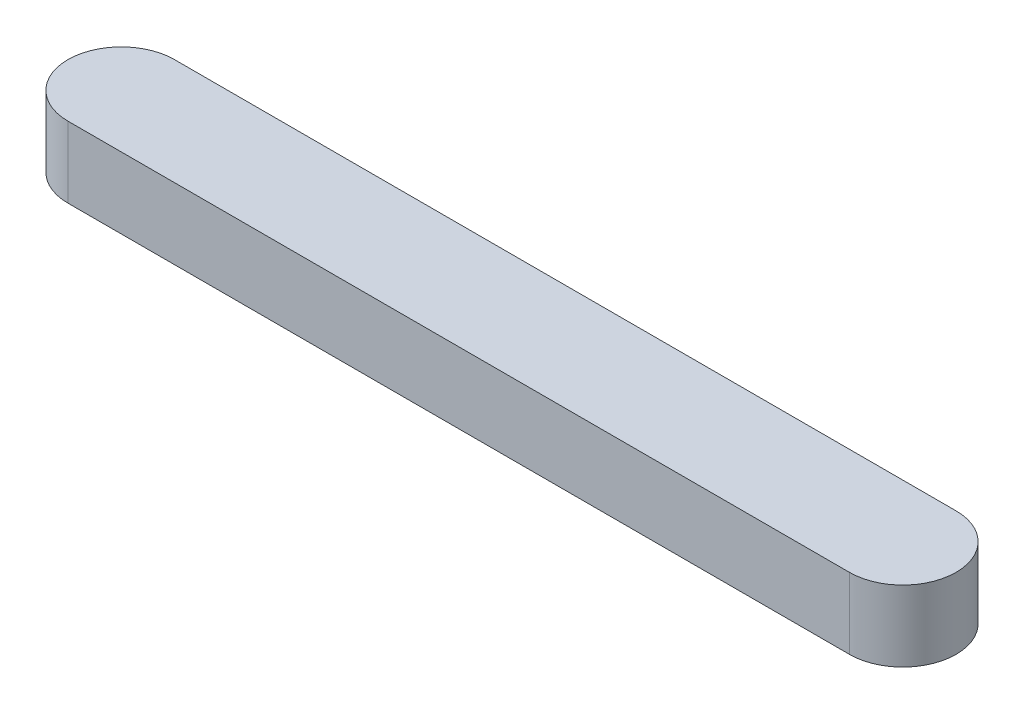
SolidWorks part; units mm, degrees
material "St-52"
ref_plane "Front Plane" through (0, 0, 0) normal (0, 0, 1) x (1, 0, 0)
ref_plane "Top Plane" through (0, 0, 0) normal (0, 1, 0) x (1, 0, 0)
ref_plane "Right Plane" through (0, 0, 0) normal (1, 0, 0) x (0, 0, -1)
sketch "Sketch1" plane through (0, 0, 0) normal (0, 1, 0) x (1, 0, 0)
  line L0 (-14.2703, 0) -> (73.7297, 0) construction
  line L1 (-14.2703, 6) -> (73.7297, 6)
  line L2 (-14.2703, -6) -> (73.7297, -6)
  arc A0 (-14.2703, 6) -> (-14.2703, -6) centre (-14.2703, 0) ccw
  arc A1 (73.7297, -6) -> (73.7297, 6) centre (73.7297, 0) ccw
  point P3 (0, 0)
  dimension "D1" = 6
  dimension "D2" = 88
extrude "Boss-Extrude1" add sketch "Sketch1" along normal mid plane 8
